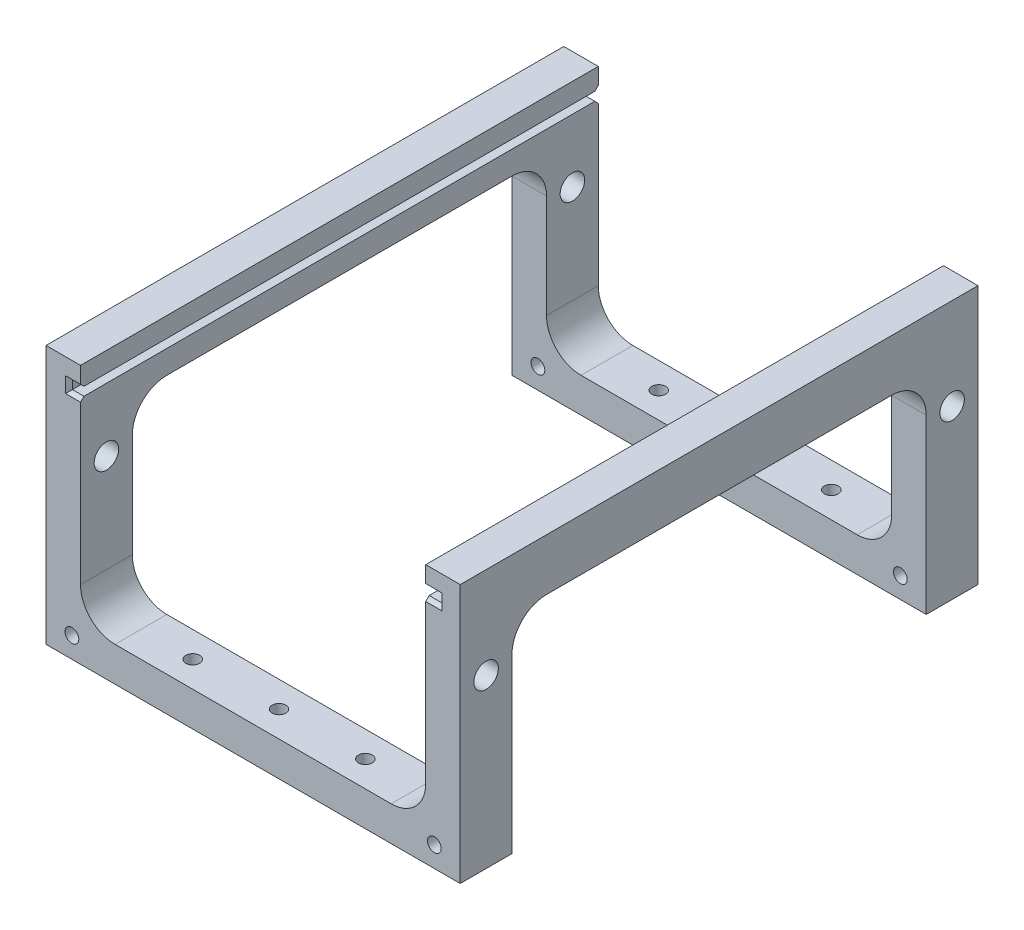
SolidWorks part; units mm, degrees
material "Commercially Pure CP-Ti UNS R50400 (SS)"
ref_plane "Front Plane" through (0, 0, 0) normal (0, 0, 1) x (1, 0, 0)
ref_plane "Top Plane" through (0, 0, 0) normal (0, 1, 0) x (1, 0, 0)
ref_plane "Right Plane" through (0, 0, 0) normal (1, 0, 0) x (0, 0, -1)
sketch "Sketch1" plane through (0, 0, 0) normal (0, 1, 0) x (1, 0, 0)
  line L1 (-60, 75) -> (60, 75)
  line L2 (-60, 75) -> (-60, -75)
  line L3 (-60, -75) -> (60, -75)
  line L4 (60, 75) -> (60, -75)
  line L5 (-60, 75) -> (60, -75) construction
  line L6 (-60, -75) -> (60, 75) construction
  point P0 (0, 0)
  dimension "D1" = 150
  dimension "D2" = 120
extrude "Boss-Extrude1" add sketch "Sketch1" along normal blind 75
sketch "Sketch3" plane through (0, 0, 75) normal (0, 0, 1) x (1, 0, 0)
  line L1 (-53.3455, 69.25) -> (53.6545, 69.25)
  line L2 (-53.3455, 69.25) -> (-53.3455, 66.75)
  line L3 (-53.3455, 66.75) -> (53.6545, 66.75)
  line L4 (53.6545, 69.25) -> (53.6545, 66.75)
  line L5 (-53.3455, 69.25) -> (53.6545, 66.75) construction
  line L6 (-53.3455, 66.75) -> (53.6545, 69.25) construction
  point P0 (0.1545, 68)
  dimension "D1" = 107
  dimension "D2" = 2.5
  dimension "D3" = 68
extrude "Cut-Extrude2" cut sketch "Sketch3" against normal through all
sketch "Sketch2" plane through (0, 75, 0) normal (0, 1, 0) x (1, 0, 0)
  line L0 (60, 75) -> (-60, 75) construction
  line L1 (-50, -75) -> (50, -75)
  line L2 (-50, -75) -> (-50, 75)
  line L3 (-50, 75) -> (50, 75)
  line L4 (50, -75) -> (50, 75)
  line L5 (-50, -75) -> (50, 75) construction
  line L6 (-50, 75) -> (50, -75) construction
  point P0 (0, 0)
  dimension "D1" = 100
extrude "Cut-Extrude1" cut sketch "Sketch2" against normal blind 65
fillet "Fillet1" radius 10 2 edges at (-50, 10, 0) (50, 10, 0)
sketch "Sketch4" plane through (0, 10, 0) normal (0, 1, 0) x (1, 0, 0)
  line L0 (40, 75) -> (-40, 75) construction
  line L1 (-40, -75) -> (40, -75) construction
  circle A0 centre (0, 67.5) radius 2
  circle A1 centre (25, 67.5) radius 2
  circle A2 centre (-25, 67.5) radius 2
  circle A3 centre (-25, -67.5) radius 2
  circle A4 centre (25, -67.5) radius 2
  circle A5 centre (0, -67.5) radius 2
  point P14 (0, 0)
  dimension "D1" = 4
  dimension "D8" = 4
  dimension "D2" = 25
  dimension "D3" = 25
  dimension "D4" = 7.5
  dimension "D5" = 25
  dimension "D6" = 25
  dimension "D7" = 7.5
extrude "Cut-Extrude3" cut sketch "Sketch4" against normal through all
sketch "Sketch5" plane through (0, 0, 75) normal (0, 0, 1) x (1, 0, 0)
  line L0 (-60, 0) -> (60, 0) construction
  circle A0 centre (-52.5, 6) radius 2
  circle A1 centre (52.5, 6) radius 2
  dimension "D2" = 4
  dimension "D1" = 6
  dimension "D3" = 52.5
  dimension "D4" = 52.5
extrude "Cut-Extrude4" cut sketch "Sketch5" against normal through all
sketch "Sketch6" plane through (60, 0, 0) normal (1, 0, 0) x (0, 0, -1)
  line L0 (-75, 0) -> (75, 0) construction
  line L2 (75, 75) -> (75, 0) construction
  line L3 (-75, 75) -> (-75, 0) construction
  circle A0 centre (67.5, 48.5) radius 3.55
  circle A1 centre (-67.5, 48.5) radius 3.55
  dimension "D1" = 7.1
  dimension "D4" = 7.1
  dimension "D2" = 48.5
  dimension "D3" = 7.5
  dimension "D5" = 7.5
extrude "Cut-Extrude5" cut sketch "Sketch6" against normal through all
chamfer "Chamfer1" distance 1 angle 45 12 edges at (51.8272, 69.25, 75) (53.6545, 68, 75) (51.8272, 66.75, 75) (51.8272, 66.75, -75) (53.6545, 68, -75) (51.8272, 69.25, -75) (-51.6728, 66.75, -75) (-51.6728, 69.25, -75) (-53.3455, 68, -75) (-51.6728, 66.75, 75) (-51.6728, 69.25, 75) (-53.3455, 68, 75)
sketch "Sketch7" plane through (60, 0, 0) normal (1, 0, 0) x (0, 0, -1)
  line L0 (-60, 0) -> (60, 0)
  line L2 (-60, 0) -> (-60, 60)
  line L3 (-60, 60) -> (60, 60)
  line L4 (60, 0) -> (60, 60)
  line L5 (-75, 0) -> (75, 0) construction
  line L8 (0, 60) -> (0, 0) construction
  line L10 (60, 30) -> (-60, 30) construction
  point P0 (0, 0)
  point P12 (60, 60)
  point P15 (-60, 60)
  dimension "D1" = 120
  dimension "D2" = 60
extrude "Cut-Extrude6" cut sketch "Sketch7" against normal through all
fillet "Fillet2" radius 10 4 edges at (55, 60, -60) (-55, 60, -60) (-55, 60, 60) (55, 60, 60)
